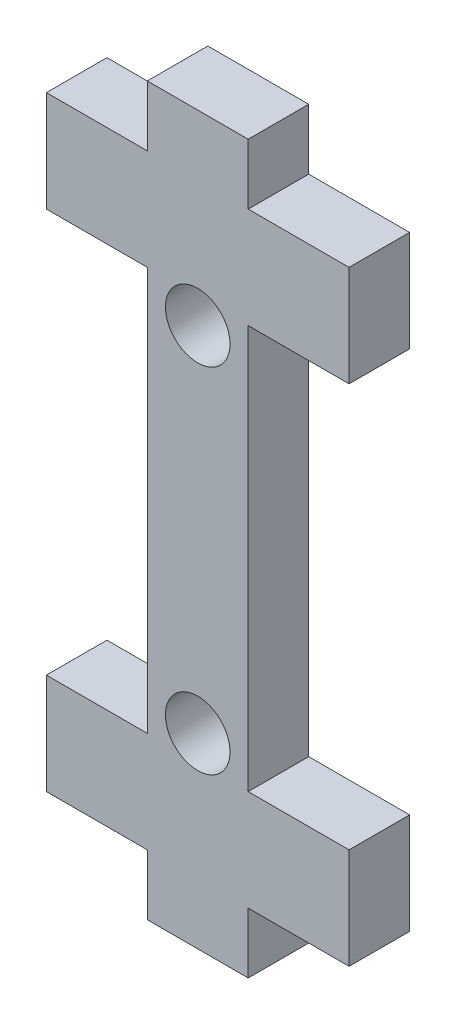
SolidWorks part; units mm, degrees
ref_plane "Front Plane" through (0, 0, 0) normal (0, 0, 1) x (1, 0, 0)
ref_plane "Top Plane" through (0, 0, 0) normal (0, 1, 0) x (1, 0, 0)
ref_plane "Right Plane" through (0, 0, 0) normal (1, 0, 0) x (0, 0, -1)
sketch "Sketch1" plane through (0, 0, 0) normal (0, 0, 1) x (1, 0, 0)
  line L0 (-2.5, 15) -> (-2.5, 18)
  line L1 (-2.5, -18) -> (2.5, -18)
  line L2 (-2.5, -18) -> (-2.5, -15)
  line L3 (-2.5, 18) -> (2.5, 18)
  line L4 (2.5, -18) -> (2.5, -15)
  line L5 (-2.5, -18) -> (2.5, 18) construction
  line L6 (-2.5, 18) -> (2.5, -18) construction
  line L7 (-7.5, 15) -> (-2.5, 15)
  line L8 (-7.5, 15) -> (-7.5, 10)
  line L9 (-7.5, 10) -> (-2.5, 10)
  line L10 (7.5, 15) -> (7.5, 10)
  line L11 (-7.5, 15) -> (7.5, 10) construction
  line L12 (-7.5, 10) -> (7.5, 15) construction
  line L13 (2.5, 15) -> (2.5, 18)
  line L14 (-2.5, 0) -> (2.5, 0) construction
  line L15 (-7.5, -10) -> (7.5, -15) construction
  line L16 (-7.5, -15) -> (7.5, -10) construction
  line L17 (7.5, -15) -> (7.5, -10)
  line L18 (-7.5, -10) -> (-2.5, -10)
  line L19 (-7.5, -15) -> (-7.5, -10)
  line L20 (-7.5, -15) -> (-2.5, -15)
  line L21 (2.5, 10) -> (7.5, 10)
  line L22 (2.5, 15) -> (7.5, 15)
  line L23 (2.5, -15) -> (7.5, -15)
  line L24 (2.5, -10) -> (2.5, 10)
  line L25 (-2.5, -10) -> (-2.5, 10)
  line L26 (2.5, -10) -> (7.5, -10)
  circle A0 centre (0, 8.75) radius 1.6
  circle A1 centre (0, -8.75) radius 1.6
  point P0 (0, 0)
  point P6 (0, 12.5)
  point P22 (0, -12.5)
  point P28 (0, 0)
  dimension "D3" = 3.2
  dimension "D1" = 36
  dimension "D2" = 5
  dimension "D4" = 15
  dimension "D5" = 5
  dimension "D6" = 8.75
  dimension "D7" = 3
extrude "Boss-Extrude1" add sketch "Sketch1" along normal blind 3
